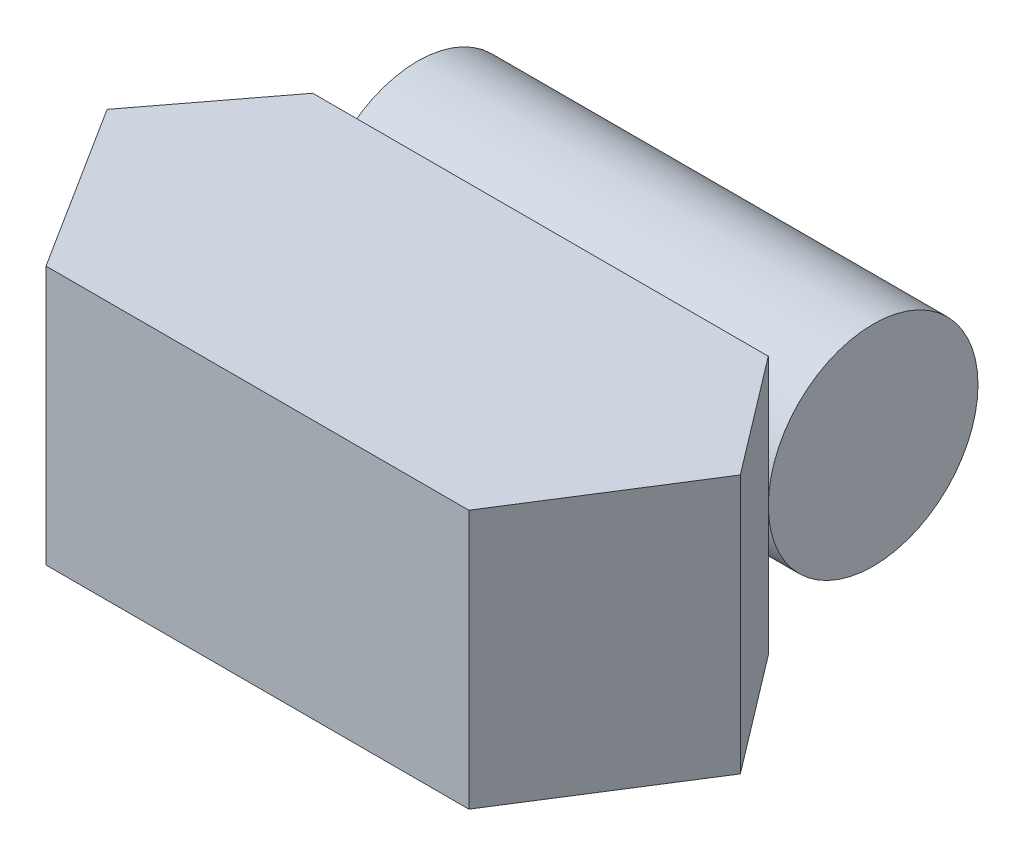
SolidWorks part; units mm, degrees
ref_plane "Front Plane" through (0, 0, 0) normal (0, 0, 1) x (1, 0, 0)
ref_plane "Top Plane" through (0, 0, 0) normal (0, 1, 0) x (1, 0, 0)
ref_plane "Right Plane" through (0, 0, 0) normal (1, 0, 0) x (0, 0, -1)
sketch "Sketch1" plane through (0, 0, 0) normal (0, 1, 0) x (1, 0, 0)
  line L0 (-13.1978, 0) -> (-18.3437, -6.7653)
  line L1 (-18.3437, -6.7653) -> (-12.25, -16.4)
  line L2 (0, -55) -> (0, 55) construction
  line L3 (18.3437, -6.7653) -> (12.25, -16.4)
  line L4 (13.1978, 0) -> (18.3437, -6.7653)
  line L5 (-13.1978, 0) -> (13.1978, 0)
  line L6 (-12.25, -16.4) -> (12.25, -16.4)
  point P8 (-78.8997, -9.4552)
  point P9 (-77.1516, 0)
  point P11 (-78.7408, -10.2498)
  point P12 (-98.6047, -8.5)
  point P13 (-93.0428, 0)
  point P14 (13.0419, 0)
  point P15 (13.1978, 0)
  dimension "D1" = 16.4
  dimension "D2" = 8.5
  dimension "D3" = 11.4
  dimension "D4" = 24.5
extrude "Boss-Extrude1" add sketch "Sketch1" along normal blind 15
ref_plane "Plane1" through (0, 7.5, 0) normal (0, 1, 0) x (1, 0, 0)
sketch "Sketch2" plane through (0, 0, 0) normal (1, 0, 0) x (0, 0, -1)
  line L0 (9.02, 7.5) -> (-9.02, 7.5) construction
  line L1 (0, 15) -> (0, 0) construction
  circle A0 centre (6.075, 7.5) radius 6.075
  point P4 (0, 0)
  dimension "D1" = 12.15
extrude "Boss-Extrude2" add sketch "Sketch2" along normal up to vertex (13.1978 mm away) and the other way up to vertex (13.1978 mm away) separate body
